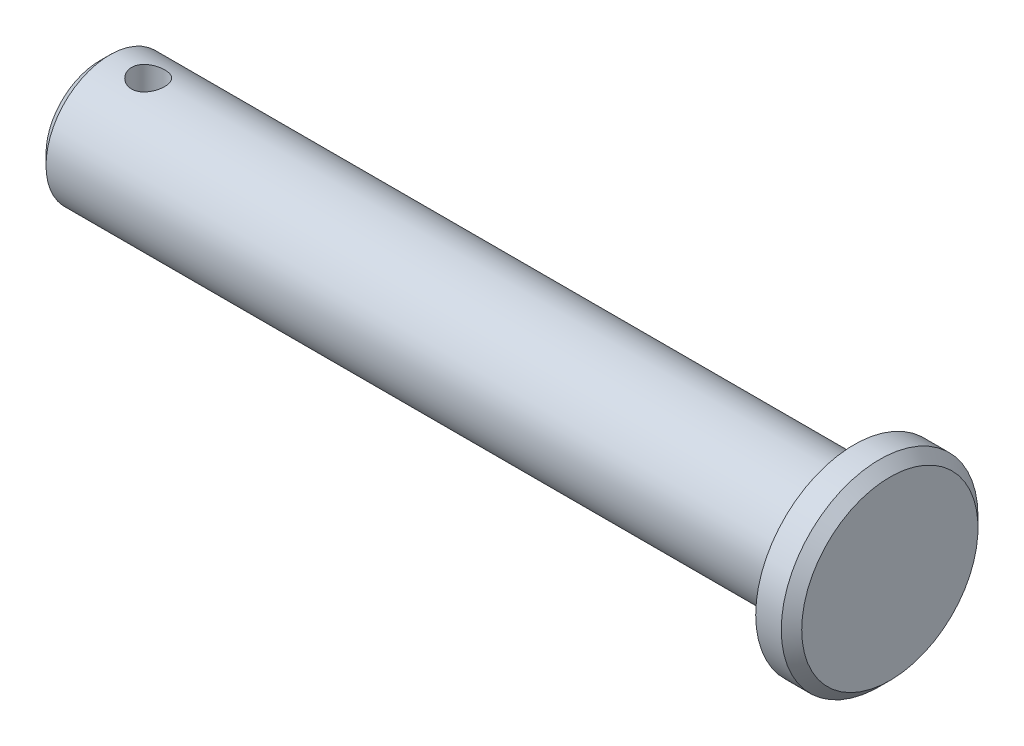
SolidWorks part; units mm, degrees
material "AISI 1020"
ref_plane "Plano frontal" through (0, 0, 0) normal (0, 0, 1) x (1, 0, 0)
ref_plane "Plano superior" through (0, 0, 0) normal (0, 1, 0) x (1, 0, 0)
ref_plane "Plano direito" through (0, 0, 0) normal (1, 0, 0) x (0, 0, -1)
sketch "Esboço1" plane through (0, 0, 0) normal (0, 0, 1) x (1, 0, 0)
  line L0 (-77.315, 0) -> (77.315, 0) construction
  line L1 (77.315, 0) -> (77.315, 17.25)
  line L2 (75.315, 19.25) -> (70.315, 19.25)
  line L3 (70.315, 19.25) -> (70.315, 12.5)
  line L4 (70.315, 12.5) -> (-75.315, 12.5)
  line L5 (-77.315, 10.5) -> (-77.315, 0)
  line L6 (-75.315, 12.5) -> (-77.315, 10.5)
  line L7 (77.315, 17.25) -> (75.315, 19.25)
  line L8 (-77.315, 0) -> (77.315, 0)
  point P4 (77.315, 19.25)
  point P7 (-77.315, 12.5)
  dimension "D1" = 38.5
  dimension "D2" = 25
  dimension "D3" = 154.63
  dimension "D4" = 7
revolve "Revolução1" add sketch "Esboço1" angle 360 about L0
sketch "Esboço2" plane through (0, 0, 0) normal (0, 1, 0) x (1, 0, 0)
  line L0 (-77.315, 0) -> (-67.815, 0) construction
  line L1 (-77.315, 10.5) -> (-77.315, -10.5) construction
  line L2 (-21.175, 0) -> (21.175, 0) construction
  circle A0 centre (-67.815, 0) radius 3.25
  dimension "D1" = 6.5
  dimension "D2" = 9.5
extrude "Corte-extrusão1" cut sketch "Esboço2" against normal through all both and the other way through all
